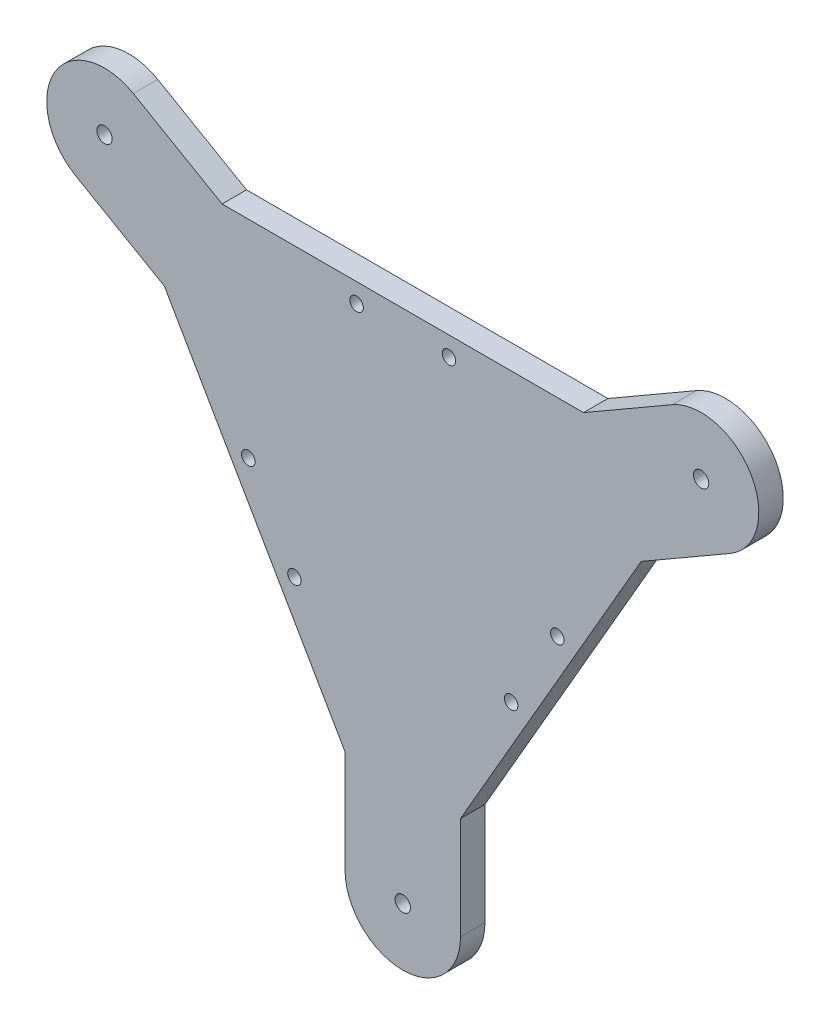
SolidWorks part; units mm, degrees
material "Acrylique (impact moyen-haut)"
ref_plane "Plan de face" through (0, 0, 0) normal (0, 0, 1) x (1, 0, 0)
ref_plane "Plan de dessus" through (0, 0, 0) normal (0, 1, 0) x (1, 0, 0)
ref_plane "Plan de droite" through (0, 0, 0) normal (1, 0, 0) x (0, 0, -1)
sketch "Esquisse2" plane through (0, 0, 0) normal (0, 0, 1) x (1, 0, 0)
  line L0 (-71.4731, 0) -> (71.4731, 0)
  line L1 (71.4731, 0) -> (0, 123.795)
  line L2 (0, 123.795) -> (-71.4731, 0)
  line L3 (-71.4731, 0) -> (0, 41.265) construction
  line L4 (0, 0) -> (71.4731, 0) construction
  line L5 (35.7365, 61.8975) -> (0, 123.795) construction
  line L6 (-35.7365, 61.8975) -> (-71.4731, 0) construction
  line L7 (0, 123.795) -> (0, 41.265) construction
  line L8 (0, 41.265) -> (71.4731, 0) construction
  point P4 (0, 0)
  dimension "D1" = 82.53
extrude "Boss.-Extru.1" add sketch "Esquisse2" along normal blind 6.35
sketch "Esquisse4" plane through (0, 0, 6.35) normal (0, 0, 1) x (1, 0, 0)
  line L0 (-71.4731, 0) -> (-49.4731, 38.1051)
  line L1 (0, 123.795) -> (-71.4731, 0) construction
  line L2 (-49.4731, 38.1051) -> (-27.4731, 0)
  line L3 (-71.4731, 0) -> (71.4731, 0) construction
  line L4 (-27.4731, 0) -> (-71.4731, 0)
  line L5 (71.4731, 0) -> (27.4731, 0)
  line L6 (27.4731, 0) -> (49.4731, 38.1051)
  line L7 (71.4731, 0) -> (0, 123.795) construction
  line L8 (49.4731, 38.1051) -> (71.4731, 0)
  line L9 (0, 123.795) -> (-22, 85.6899)
  line L10 (-22, 85.6899) -> (22, 85.6899)
  line L11 (22, 85.6899) -> (0, 123.795)
  dimension "D1" = 44
  dimension "D2" = 44
  dimension "D3" = 44
  dimension "D4" = 44
  dimension "D5" = 44
extrude "Enlèv. mat.-Extru.2" cut sketch "Esquisse4" against normal through all
sketch "Esquisse5" plane through (0, 0, 6.35) normal (0, 0, 1) x (1, 0, 0)
  line L1 (-27.4731, 0) -> (-49.4731, 38.1051) construction
  line L2 (49.4731, 38.1051) -> (27.4731, 0) construction
  line L3 (-22, 85.6899) -> (22, 85.6899) construction
  line L4 (-40.1429, 31.9449) -> (-28.1429, 11.1603) construction
  line L5 (-34.1429, 21.5526) -> (-80.958, -5.4761) construction
  line L8 (40.1429, 31.9449) -> (28.1429, 11.1603) construction
  line L9 (28.1429, 11.1603) -> (34.1429, 21.5526) construction
  line L10 (34.1429, 21.5526) -> (80.4017, -5.1549) construction
  line L11 (-12, 80.6899) -> (12, 80.6899) construction
  line L12 (12, 80.6899) -> (0, 80.6899) construction
  line L13 (0, 80.6899) -> (0, 169.9581) construction
  circle A0 centre (-40.1429, 31.9449) radius 1.75
  circle A1 centre (-28.1429, 11.1603) radius 1.75
  circle A2 centre (28.1429, 11.1603) radius 1.75
  circle A3 centre (40.1429, 31.9449) radius 1.75
  circle A4 centre (-12, 80.6899) radius 1.75
  circle A5 centre (12, 80.6899) radius 1.75
  point P14 (-38.4731, 19.0526)
  point P21 (0, 85.6899)
  dimension "D8" = 3.5
  dimension "D1" = 24
  dimension "D2" = 24
  dimension "D3" = 24
  dimension "D4" = 5
  dimension "D5" = 5
  dimension "D6" = 5
  dimension "D7" = 5
extrude "Enlèv. mat.-Extru.3" cut sketch "Esquisse5" against normal through all
sketch "Esquisse9" plane through (0, 0, 0) normal (0, 0, -1) x (-1, 0, 0)
  line L0 (-35.7365, 61.8975) -> (-77.5, 86.0096) construction
  line L1 (-49.4731, 38.1051) -> (-22, 85.6899) construction
  line L3 (27.4731, 0) -> (-27.4731, 0) construction
  line L4 (0, 0) -> (0, -48.2243) construction
  line L6 (22, 85.6899) -> (49.4731, 38.1051) construction
  line L7 (35.7365, 61.8975) -> (77.5, 86.0096) construction
  circle A0 centre (77.5, 86.0096) radius 2
  circle A1 centre (-77.5, 86.0096) radius 2
  circle A2 centre (0, -48.2243) radius 2
  point P15 (0, 0)
  point P16 (0, 0)
  point P17 (0, 0)
  point P18 (0, 0)
  dimension "D1" = 4
  dimension "D2" = 155
sketch "Esquisse10" plane through (0, 0, 0) normal (0, 0, -1) x (-1, 0, 0)
  line L0 (49.4731, 38.1051) -> (61.9462, 59.7091)
  line L1 (61.9462, 59.7091) -> (85, 73.0193)
  line L2 (70, 99) -> (46.9462, 85.6899)
  line L3 (46.9462, 85.6899) -> (22, 85.6899)
  line L4 (22, 85.6899) -> (49.4731, 38.1051)
  line L5 (-22, 85.6899) -> (-46.9462, 85.6899)
  line L6 (-46.9462, 85.6899) -> (-70, 99)
  line L7 (-85, 73.0193) -> (-61.9462, 59.7091)
  line L8 (-61.9462, 59.7091) -> (-49.4731, 38.1051)
  line L9 (-49.4731, 38.1051) -> (-22, 85.6899)
  line L10 (-27.4731, 0) -> (-15, -21.604)
  line L11 (-15, -21.604) -> (-15, -48.2243)
  line L12 (15, -48.2243) -> (15, -21.604)
  line L13 (15, -21.604) -> (27.4731, 0)
  line L14 (27.4731, 0) -> (-27.4731, 0)
  line L15 (-70, 99) -> (-85, 73.0193) construction
  line L16 (15, -48.2243) -> (-15, -48.2243) construction
  line L17 (85, 73.0193) -> (70, 99) construction
  arc A0 (85, 73.0193) -> (70, 99) centre (77.5, 86.0096) ccw
  arc A1 (-70, 99) -> (-85, 73.0193) centre (-77.5, 86.0096) ccw
  arc A2 (-15, -48.2243) -> (15, -48.2243) centre (0, -48.2243) ccw
  dimension "D1" = 60
  dimension "D2" = 60
  dimension "D3" = 30
extrude "Boss.-Extru.2" add sketch "Esquisse10" against normal up to surface (6.35 mm away) up to face at (-38.3929, 31.9449, 6.35)
sketch "Esquisse11" plane through (0, 0, 6.35) normal (0, 0, 1) x (1, 0, 0)
  circle A0 centre (-77.5, 86.0096) radius 2
  circle A1 centre (77.5, 86.0096) radius 2
  circle A2 centre (0, -48.2243) radius 2
extrude "Enlèv. mat.-Extru.4" cut sketch "Esquisse11" against normal through all
